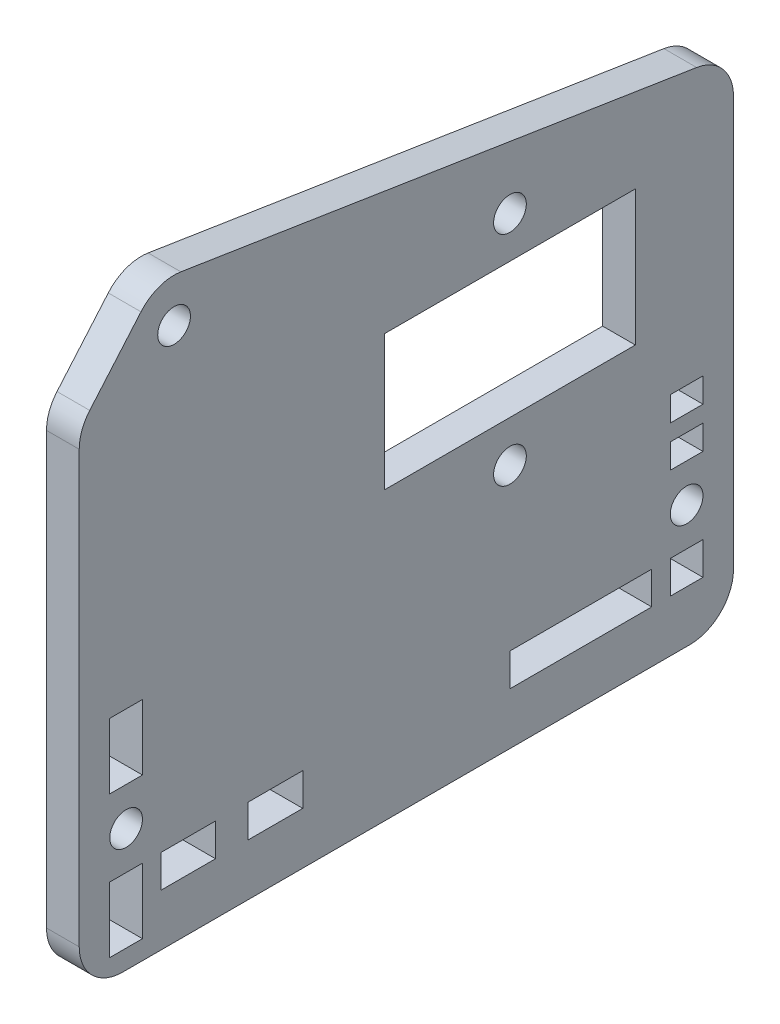
SolidWorks part; units mm, degrees
material "Acrílico (médio-alto impacto)"
ref_plane "Plano frontal" through (0, 0, 0) normal (0, 0, 1) x (1, 0, 0)
ref_plane "Plano superior" through (0, 0, 0) normal (0, 1, 0) x (1, 0, 0)
ref_plane "Plano direito" through (0, 0, 0) normal (1, 0, 0) x (0, 0, -1)
sketch "Esboço1" plane through (0, 0, 0) normal (1, 0, 0) x (0, 0, -1)
  line L0 (0, 0) -> (60, 0)
  line L1 (60, 0) -> (60, 45)
  line L4 (0, 45) -> (0, 0)
  line L5 (60, 45) -> (9.32, 52.9517)
  line L6 (5.6637, 51.604) -> (0, 45)
  arc A0 (9.32, 52.9517) -> (5.6637, 51.604) centre (8.7, 49) ccw
  point P4 (8.7, 49)
  dimension "D6" = 4
  dimension "D1" = 60
  dimension "D2" = 45
  dimension "D3" = 4
  dimension "D4" = 8.7
  dimension "D5" = 53
sketch "Esboço6" plane through (0, 0, 0) normal (1, 0, 0) x (0, 0, -1)
  line L0 (30, 0) -> (30, 29.3628) construction
  line L1 (0, 0) -> (60, 0) construction
  line L2 (4.3, 11.25) -> (55.7, 11.25) construction
  line L3 (4.3, 20.75) -> (4.3, 1.75) construction
  line L4 (55.7, 20.75) -> (55.7, 1.75) construction
  line L6 (2.8, 14.75) -> (5.8, 14.75)
  line L7 (2.8, 14.75) -> (2.8, 20.75)
  line L8 (2.8, 20.75) -> (5.8, 20.75)
  line L9 (5.8, 14.75) -> (5.8, 20.75)
  line L10 (4.3, 20.75) -> (4.3, 14.75) construction
  line L11 (2.8, 17.75) -> (5.8, 17.75) construction
  line L12 (2.8, 7.75) -> (5.8, 7.75)
  line L13 (2.8, 7.75) -> (2.8, 1.75)
  line L14 (2.8, 1.75) -> (5.8, 1.75)
  line L15 (5.8, 7.75) -> (5.8, 1.75)
  line L16 (4.3, 1.75) -> (4.3, 7.75) construction
  line L17 (2.8, 4.75) -> (5.8, 4.75) construction
  line L18 (54.2, 18.5) -> (57.2, 18.5)
  line L19 (54.2, 18.5) -> (54.2, 20.75)
  line L20 (54.2, 20.75) -> (57.2, 20.75)
  line L21 (57.2, 18.5) -> (57.2, 20.75)
  line L22 (55.7, 20.75) -> (55.7, 18.5) construction
  line L23 (54.2, 19.625) -> (57.2, 19.625) construction
  line L24 (54.2, 14.75) -> (57.2, 14.75)
  line L25 (54.2, 14.75) -> (54.2, 17)
  line L26 (54.2, 17) -> (57.2, 17)
  line L27 (57.2, 14.75) -> (57.2, 17)
  line L28 (55.7, 17) -> (55.7, 14.75) construction
  line L29 (54.2, 15.875) -> (57.2, 15.875) construction
  line L30 (54.2, 7.75) -> (57.2, 7.75)
  line L31 (54.2, 7.75) -> (54.2, 4.75)
  line L32 (54.2, 4.75) -> (57.2, 4.75)
  line L33 (57.2, 7.75) -> (57.2, 4.75)
  line L34 (55.7, 4.75) -> (55.7, 7.75) construction
  line L35 (54.2, 6.25) -> (57.2, 6.25) construction
  point P4 (4.3, 17.75)
  point P7 (30, 11.25)
  point P10 (4.3, 11.25)
  point P13 (55.7, 11.25)
  point P17 (4.3, 4.75)
  point P21 (55.7, 15.875)
  point P24 (55.7, 19.625)
  point P30 (55.7, 6.25)
  dimension "D1" = 19
  dimension "D2" = 51.4
  dimension "D3" = 11.25
  dimension "D4" = 3
  dimension "D5" = 6
  dimension "D6" = 6
  dimension "D7" = 2.25
  dimension "D8" = 3
  dimension "D9" = 3
sketch "Esboço9" plane through (0, 0, 0) normal (1, 0, 0) x (0, 0, -1)
  line L0 (6, 4.75) -> (54, 4.75) construction
  line L1 (30, 0) -> (30, 29.3628) construction
  line L3 (12.5, 7.75) -> (15.5, 7.75) construction
  line L4 (7.5, 4.75) -> (12.5, 4.75)
  line L5 (7.5, 4.75) -> (7.5, 7.75)
  line L6 (7.5, 7.75) -> (12.5, 7.75)
  line L7 (12.5, 4.75) -> (12.5, 7.75)
  line L8 (15.5, 4.75) -> (20.5, 4.75)
  line L9 (15.5, 4.75) -> (15.5, 7.75)
  line L10 (15.5, 7.75) -> (20.5, 7.75)
  line L11 (20.5, 4.75) -> (20.5, 7.75)
  line L12 (2.8, 7.75) -> (5.8, 7.75) construction
  line L13 (2.8, 1.75) -> (5.8, 1.75) construction
  line L14 (52.5, 4.75) -> (39.5, 4.75)
  line L15 (52.5, 4.75) -> (52.5, 7.75)
  line L16 (52.5, 7.75) -> (39.5, 7.75)
  line L17 (39.5, 4.75) -> (39.5, 7.75)
  point P3 (30, 4.75)
  dimension "D1" = 48
  dimension "D2" = 3
  dimension "D3" = 5
  dimension "D4" = 1.5
  dimension "D5" = 1.5
  dimension "D6" = 13
  dimension "D7" = 3
extrude "Ressalto-extrusão1" add sketch "Esboço1" along normal blind 3
sketch "Perfil Corte" plane through (0, 41.4004, -36.0805) normal (-1, 0, 0) x (0, 0, 1)
  line L0 (-3.4195, -18.9004) -> (-3.4195, 1.0996) construction
  line L1 (-14.9195, -15.1004) -> (8.0805, -15.1004)
  line L2 (-14.9195, -15.1004) -> (-14.9195, -2.7004)
  line L3 (-14.9195, -2.7004) -> (8.0805, -2.7004)
  line L4 (8.0805, -15.1004) -> (8.0805, -2.7004)
  line L5 (-3.4195, -2.7004) -> (-3.4195, -15.1004) construction
  line L6 (-14.9195, -8.9004) -> (8.0805, -8.9004) construction
  line L7 (8.0805, -8.9004) -> (-23.9195, -8.9004) construction
  line L8 (-23.9195, 3.5996) -> (-23.9195, -41.4004) construction
  line L9 (-23.9195, -41.4004) -> (36.0805, -41.4004) construction
  point P0 (-3.4195, -8.9004)
  point P7 (-3.4195, -8.9004)
  dimension "D1" = 23
  dimension "entre furos" = 20
  dimension "D2" = 12.4
  dimension "Afastamento Lateral" = 20.5
  dimension "Posicionamento Altura" = 32.5
extrude "Corte Principal" cut sketch "Perfil Corte" against normal through all
hole_wizard "Furo de diâmetro Ø3.0 (3)1" positions "Esboço4" profile "Esboço5" hole size "Ø3.0" standard "ISO" end condition through all
sketch "Esboço4" plane through (0, -50, -154.4799) normal (-1, 0, 0) x (0, 0, 1)
  point P0 (114.9799, 92.5)
  point P3 (114.9799, 72.5)
sketch "Esboço5" plane through (0, 42.5, -39.5) normal (0, 1, 0) x (0, 0, 1)
  line L0 (0, 0) -> (0, 3)
  line L1 (0, 3) -> (1.5, 3)
  line L2 (1.5, 3) -> (1.5, 0)
  line L5 (1.5, 0) -> (0, 0)
  line L11 (0, -6.35) -> (0, 107.95) construction
  dimension "Thru Hole Dia." = 3
  dimension "Thru Hole Depth" = 3
other "Furos Motor<1>"
extrude "Corte-extrusão1" cut sketch "Esboço6" along normal through all
hole_wizard "Furo de diâmetro Ø3.0 (3)2" positions "Esboço7" profile "Esboço8" hole size "Ø3.0" standard "ISO" end condition through all
sketch "Esboço7" plane through (3, 0, 0) normal (1, 0, 0) x (0, 0, -1)
  point P0 (4.3, 11.25)
  point P3 (55.7, 11.25)
sketch "Esboço8" plane through (3, 11.25, -4.3) normal (0, 1, 0) x (0, 0, -1)
  line L0 (0, 0) -> (0, 3)
  line L1 (0, 3) -> (1.5, 3)
  line L2 (1.5, 3) -> (1.5, 0)
  line L5 (1.5, 0) -> (0, 0)
  line L11 (0, -6.35) -> (0, 107.95) construction
  dimension "Thru Hole Dia." = 3
  dimension "Thru Hole Depth" = 3
hole_wizard "Furo de diâmetro Ø3.0 (3)3" positions "Esboço10" profile "Esboço11" hole size "Ø3.0" standard "ISO" end condition through all
sketch "Esboço10" plane through (0, 0, 0) normal (-1, 0, 0) x (0, 0, 1)
  point P0 (-8.7, 49)
sketch "Esboço11" plane through (0, 49, -8.7) normal (0, 1, 0) x (0, 0, 1)
  line L0 (0, 0) -> (0, 3)
  line L1 (0, 3) -> (1.5, 3)
  line L2 (1.5, 3) -> (1.5, 0)
  line L5 (1.5, 0) -> (0, 0)
  line L11 (0, -6.35) -> (0, 107.95) construction
  dimension "Thru Hole Dia." = 3
  dimension "Thru Hole Depth" = 3
extrude "Corte-extrusão2" cut sketch "Esboço9" along normal through all
fillet "Filete1" radius 4 4 edges at (1.5, 45, -60) (1.5, 45, 0) (1.5, 0, -60) (1.5, 0, 0)
